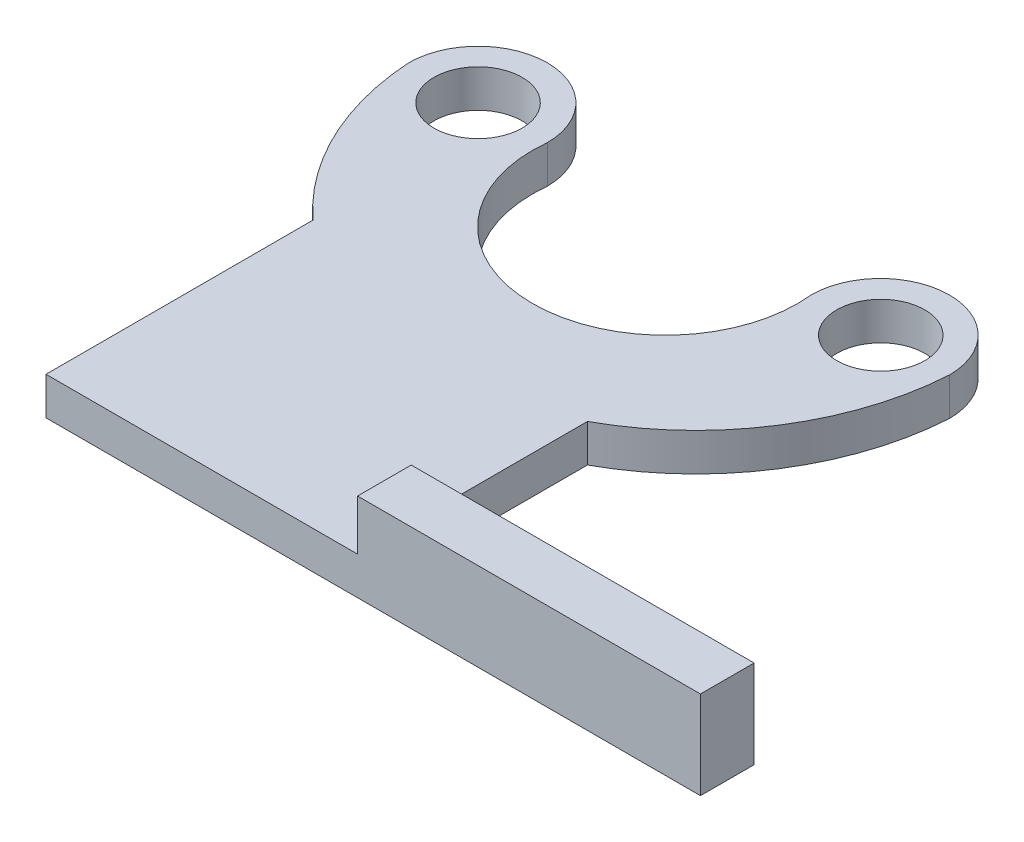
SolidWorks part; units mm, degrees
ref_plane "前视基准面" through (0, 0, 0) normal (0, 0, 1) x (1, 0, 0)
ref_plane "上视基准面" through (0, 0, 0) normal (0, 1, 0) x (1, 0, 0)
ref_plane "右视基准面" through (0, 0, 0) normal (1, 0, 0) x (0, 0, -1)
other "Configuration Table"
sketch "草图1" plane through (0, 0, 0) normal (0, 1, 0) x (1, 0, 0)
  line L0 (-7.2391, -7.3141) -> (-7.2391, -17.9247)
  line L1 (-7.2391, -17.9247) -> (18.7609, -17.9247)
  line L2 (18.7609, -15.7928) -> (18.7609, -17.9247)
  line L3 (18.7609, -15.7928) -> (5.1388, -15.7928)
  line L4 (5.1388, -15.7928) -> (5.1388, -8.7928)
  circle A1 centre (0, 0) radius 8 construction
  circle A2 centre (-8, 0) radius 1.75
  circle A3 centre (0, 8) radius 1.75 construction
  circle A4 centre (0, 0) radius 5 construction
  arc A5 (-5.25, 0) -> (-10.75, 0) centre (-8, 0) ccw
  circle A6 centre (8, 0) radius 1.75
  circle A7 centre (0, -8) radius 1.75 construction
  arc A8 (10.7305, 0) -> (5.2305, 0) centre (7.9805, 0) ccw
  arc A9 (-5.25, 0) -> (5.2305, 0) centre (-0.0097, -0.5576) ccw
  arc A10 (10.7305, 0) -> (5.1388, -8.7928) centre (-0.0097, 0.6558) cw
  arc A11 (-7.2391, -7.3141) -> (-10.75, 0) centre (-0.0097, 0.6558) cw
  point P9 (0, 0)
  point P10 (-36.5235, -4.772)
  point P18 (-0.0097, 0)
  point P22 (-7.2391, -27.3141)
  dimension "D4" = 10
  dimension "D5" = 5.5
  dimension "D6" = 2
  dimension "D7" = 2.1319
  dimension "D8" = 7
  dimension "D10" = 26
  dimension "D3" = 4
extrude "凸台-拉伸1" add sketch "草图1" along normal blind 1.5
sketch "草图2" plane through (0, 1.5, 0) normal (0, 1, 0) x (1, 0, 0)
  line L1 (5.1388, -15.7928) -> (18.7609, -15.7928)
  line L2 (5.1388, -15.7928) -> (5.1388, -17.9247)
  line L3 (5.1388, -17.9247) -> (18.7609, -17.9247)
  line L4 (18.7609, -15.7928) -> (18.7609, -17.9247)
extrude "凸台-拉伸2" add sketch "草图2" along normal blind 2
